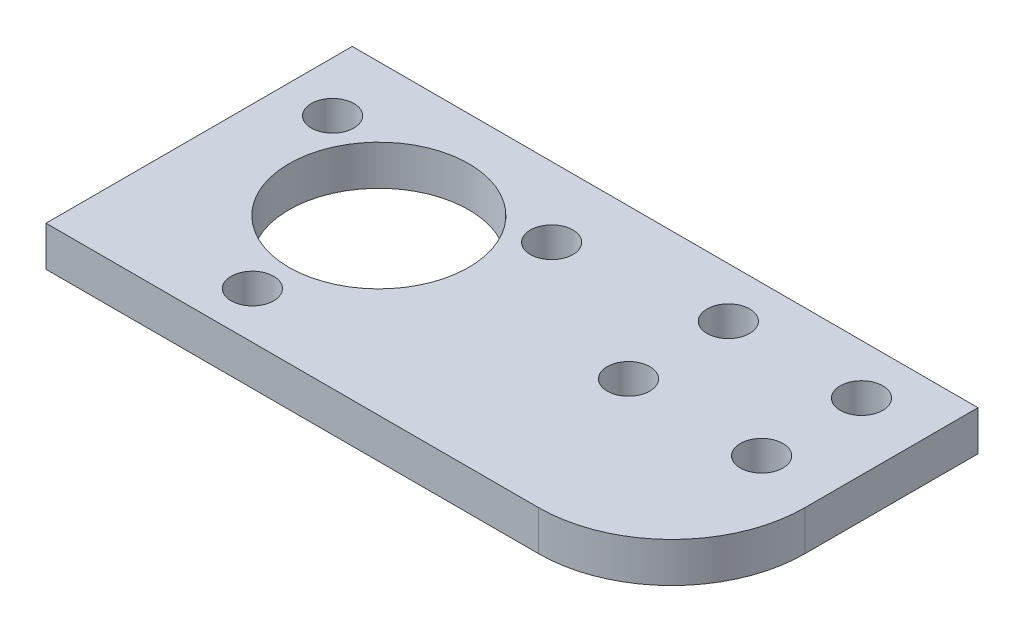
SolidWorks part; units mm, degrees
ref_plane "前视基准面" through (0, 0, 0) normal (0, 0, 1) x (1, 0, 0)
ref_plane "上视基准面" through (0, 0, 0) normal (0, 1, 0) x (1, 0, 0)
ref_plane "右视基准面" through (0, 0, 0) normal (1, 0, 0) x (0, 0, -1)
other "Configuration Table"
sketch "草图1" plane through (0, 0, 0) normal (0, 1, 0) x (1, 0, 0)
  line L1 (-27.5, -10) -> (27.5, -10)
  line L2 (-27.5, -10) -> (-27.5, 10)
  line L3 (-27.5, 10) -> (27.5, 10)
  line L4 (27.5, -10) -> (27.5, 10)
  line L5 (-27.5, -10) -> (27.5, 10) construction
  line L6 (-27.5, 10) -> (27.5, -10) construction
  point P0 (0, 0)
  dimension "D1" = 20
  dimension "D2" = 55
extrude "凸台-拉伸1" add sketch "草图1" along normal blind 3
sketch "草图2" plane through (0, 3, 0) normal (0, 1, 0) x (1, 0, 0)
  line L0 (-27.5, -10) -> (27.5, -10) construction
  line L1 (-27.5, 10) -> (2.5, 10)
  line L2 (-27.5, 10) -> (-27.5, -10)
  line L3 (-27.5, -10) -> (2.5, -10)
  line L4 (2.5, 10) -> (2.5, -10)
  line L5 (-7.5, 0) -> (-7.5, -9.5) construction
  line L6 (-7.5, 0) -> (0.7272, 4.75) construction
  line L7 (-7.5, 0) -> (-15.7272, 4.75) construction
  circle A0 centre (-7.5, 0) radius 9.5 construction
  circle A1 centre (-15.7272, 4.75) radius 1.6
  circle A2 centre (-7.5, -9.5) radius 1.6
  circle A3 centre (0.7272, 4.75) radius 1.6
  circle A4 centre (-7.5, 0) radius 6.75
  dimension "D2" = 19
  dimension "D5" = 3.2
  dimension "D7" = 13.5
  dimension "D1" = 30
  dimension "D3" = 120
  dimension "D4" = 120
  dimension "D6" = 10
  dimension "D8" = 20
extrude "切除-拉伸1" cut sketch "草图2" against normal through all contours A1 | A2 | A3 | A4
sketch "草图3" plane through (0, 3, 0) normal (0, 1, 0) x (1, 0, 0)
  line L1 (30, 10) -> (0, 10)
  line L2 (30, 10) -> (30, -10)
  line L3 (30, -10) -> (0, -10)
  line L4 (0, 10) -> (0, -10)
  dimension "D1" = 30
  dimension "D2" = 20
sketch "草图4" plane through (0, 3, 0) normal (0, 1, 0) x (1, 0, 0)
  line L0 (30, -10) -> (0, -10) construction
  line L1 (27.5, 10) -> (17.5, 10) construction
  line L2 (27.5, 10) -> (27.5, -10) construction
  line L3 (27.5, -10) -> (17.5, -10) construction
  line L4 (17.5, 10) -> (17.5, -10) construction
  line L5 (22.5, 6.25) -> (22.5, -1.25) construction
  line L6 (17.5, 10) -> (17.5, -5) construction
  line L7 (12.5, 6.25) -> (12.5, -1.25) construction
  circle A0 centre (22.5, 6.25) radius 1.6
  circle A1 centre (12.5, 6.25) radius 1.6
  circle A2 centre (22.5, -1.25) radius 1.6
  circle A3 centre (12.5, -1.25) radius 1.6
  dimension "D2" = 3.2
  dimension "D8" = 3.2
  dimension "D9" = 3.2
  dimension "D1" = 10
  dimension "D3" = 5
  dimension "D4" = 3.75
  dimension "D5" = 7.5
  dimension "D6" = 10
  dimension "D7" = 7.5
extrude "切除-拉伸2" cut sketch "草图4" against normal through all
sketch "草图5" plane through (0, 3, 0) normal (0, 1, 0) x (1, 0, 0)
  line L0 (-27.5, -10) -> (-27.5, -13)
  line L1 (-27.5, -13) -> (0, -13)
  line L3 (-27.5, -10) -> (27.5, -10)
  line L4 (27.5, -10) -> (27.5, -13)
  line L5 (27.5, -13) -> (0, -13)
  line L6 (27.5, -10) -> (27.5, 10) construction
  dimension "D1" = 3
extrude "凸台-拉伸2" add sketch "草图5" against normal blind 3
sketch "草图6" plane through (0, 3, 0) normal (0, 1, 0) x (1, 0, 0)
  circle A0 centre (-7.5, -9.5) radius 1.6
  dimension "D1" = 3.2
extrude "切除-拉伸3" cut sketch "草图6" against normal through all
sketch "草图7" plane through (0, 3, 0) normal (0, 1, 0) x (1, 0, 0)
  line L0 (-27.5, -13) -> (27.5, -13) construction
  line L1 (-27.5, 10) -> (-19.5, 10)
  line L2 (-27.5, 10) -> (-27.5, -13)
  line L3 (-27.5, -13) -> (-19.5, -13)
  line L4 (-19.5, 10) -> (-19.5, -13)
  dimension "D1" = 8
extrude "切除-拉伸4" cut sketch "草图7" against normal through all
fillet "圆角1" radius 10 1 edges at (27.5, 1.5, 13)
